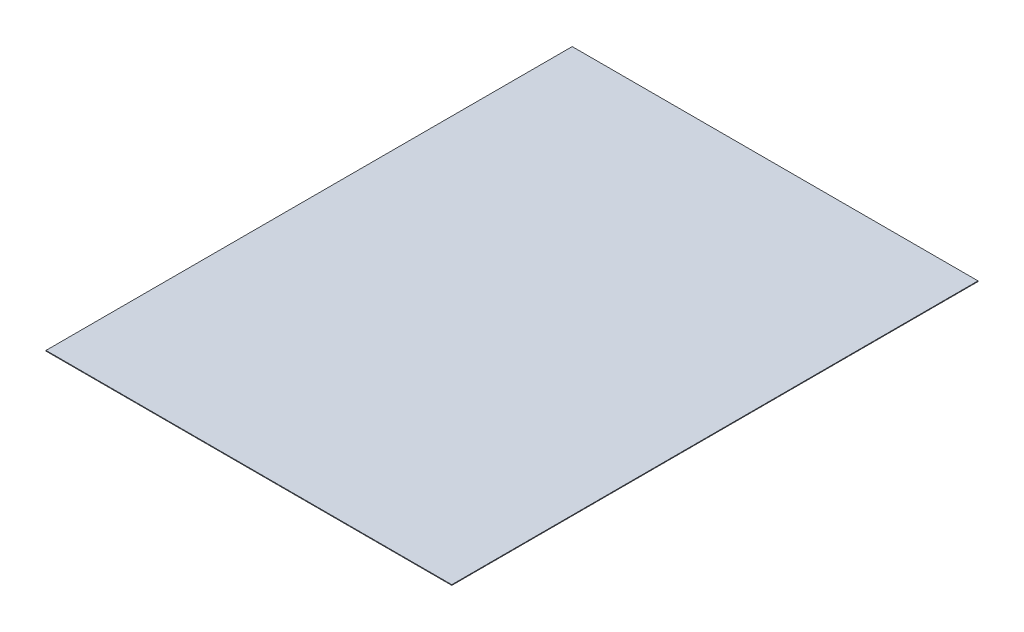
SolidWorks part; units mm, degrees
ref_plane "Front Plane" through (0, 0, 0) normal (0, 0, 1) x (1, 0, 0)
ref_plane "Top Plane" through (0, 0, 0) normal (0, 1, 0) x (1, 0, 0)
ref_plane "Right Plane" through (0, 0, 0) normal (1, 0, 0) x (0, 0, -1)
other "Configuration Table"
sketch "Sketch1" plane through (0, 0, 0) normal (0, 0, 1) x (1, 0, 0)
  line L1 (42.5, 241.5) -> (657.5, 241.5)
  line L2 (42.5, 241.5) -> (42.5, 242.5)
  line L3 (42.5, 242.5) -> (657.5, 242.5)
  line L4 (657.5, 241.5) -> (657.5, 242.5)
extrude "TOPPING_ic_alt_1" add sketch "Sketch1" against normal blind 797.5 separate body
